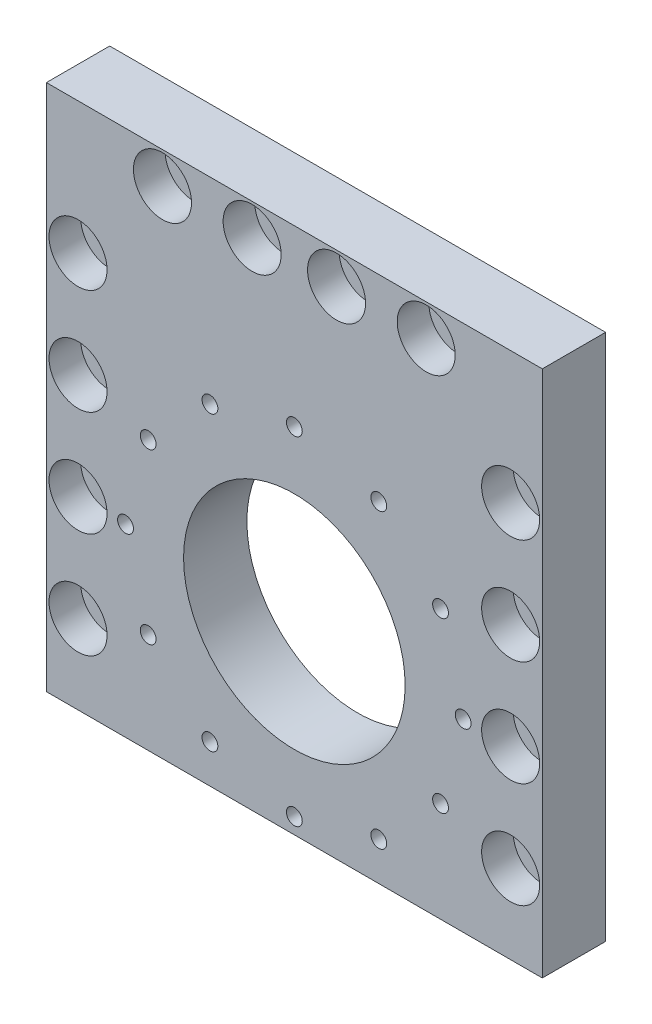
SolidWorks part; units mm, degrees
ref_plane "前视基准面" through (0, 0, 0) normal (0, 0, 1) x (1, 0, 0)
ref_plane "上视基准面" through (0, 0, 0) normal (0, 1, 0) x (1, 0, 0)
ref_plane "右视基准面" through (0, 0, 0) normal (1, 0, 0) x (0, 0, -1)
sketch "草图1" plane through (0, 0, 0) normal (0, 0, 1) x (1, 0, 0)
  line L1 (35, -35) -> (-35, -35)
  line L2 (35, -35) -> (35, 35)
  line L3 (35, 35) -> (-35, 35)
  line L4 (-35, -35) -> (-35, 35)
  line L5 (35, -35) -> (-35, 35) construction
  line L6 (35, 35) -> (-35, -35) construction
  circle A0 centre (0, 0) radius 21
  circle A1 centre (32, 0) radius 1.5
  circle A2 centre (27.7128, -16) radius 1.5
  circle A3 centre (16, -27.7128) radius 1.5
  circle A4 centre (0, -32) radius 1.5
  circle A5 centre (-16, -27.7128) radius 1.5
  circle A6 centre (-27.7128, -16) radius 1.5
  circle A7 centre (-32, 0) radius 1.5
  circle A8 centre (-27.7128, 16) radius 1.5
  circle A9 centre (-16, 27.7128) radius 1.5
  circle A10 centre (0, 32) radius 1.5
  circle A11 centre (16, 27.7128) radius 1.5
  circle A12 centre (27.7128, 16) radius 1.5
  point P0 (0, 0)
  dimension "D3" = 42
  dimension "D4" = 3
  dimension "D1" = 70
  dimension "D2" = 70
  dimension "D5" = 32
  dimension "D6" = 12
extrude "凸台-拉伸1" add sketch "草图1" along normal blind 12
sketch "草图3" plane through (0, 35, 0) normal (0, 1, 0) x (1, 0, 0)
  line L1 (-35, 0) -> (35, 0)
  line L2 (-35, 0) -> (-35, -12)
  line L3 (-35, -12) -> (35, -12)
  line L4 (35, 0) -> (35, -12)
extrude "凸台-拉伸2" add sketch "草图3" along normal blind 30
sketch "草图4" plane through (0, 0, 0) normal (0, 0, -1) x (-1, 0, 0)
  line L0 (-35, 65) -> (35, 65) construction
  line L1 (-35, -35) -> (-35, 65) construction
  line L2 (0, 61.4377) -> (0, 44.3718) construction
  circle A0 centre (-25, 59) radius 3
  circle A1 centre (-8, 59) radius 3
  circle A2 centre (25, 59) radius 3
  circle A3 centre (8, 59) radius 3
  dimension "D1" = 6
  dimension "D2" = 6
  dimension "D3" = 6
  dimension "D4" = 10
  dimension "D5" = 6
  dimension "D6" = 17
extrude "切除-拉伸2" cut sketch "草图4" against normal blind 12
sketch "草图7" plane through (0, 0, 12) normal (0, 0, 1) x (1, 0, 0)
  circle A2 centre (-25, 59) radius 5.5
  circle A3 centre (-25, 59) radius 5.5
  circle A5 centre (-8, 59) radius 5.5
  circle A6 centre (-8, 59) radius 5.5
  circle A8 centre (8, 59) radius 5.5
  circle A9 centre (8, 59) radius 5.5
  circle A11 centre (25, 59) radius 5.5
  circle A12 centre (25, 59) radius 5.5
  dimension "D1" = 2.5
  dimension "D2" = 2.5
  dimension "D3" = 2.5
  dimension "D4" = 2.5
extrude "切除-拉伸6" cut sketch "草图7" against normal blind 6
sketch "草图8" plane through (35, 0, 0) normal (1, 0, 0) x (0, 0, -1)
  line L1 (-12, 65) -> (0, 65)
  line L2 (-12, 65) -> (-12, -35)
  line L3 (-12, -35) -> (0, -35)
  line L4 (0, 65) -> (0, -35)
extrude "凸台-拉伸3" add sketch "草图8" along normal blind 12
sketch "草图11" plane through (-35, 0, 0) normal (-1, 0, 0) x (0, 0, 1)
  line L1 (0, 65) -> (12, 65)
  line L2 (0, 65) -> (0, -35)
  line L3 (0, -35) -> (12, -35)
  line L4 (12, 65) -> (12, -35)
extrude "凸台-拉伸4" add sketch "草图11" along normal blind 12
sketch "草图12" plane through (0, 0, 12) normal (0, 0, 1) x (1, 0, 0)
  line L0 (41, 54.0546) -> (41, -24.676) construction
  line L1 (-47, -35) -> (47, -35) construction
  line L2 (0, 0) -> (0, 36.0161) construction
  line L3 (47, 65) -> (47, -35) construction
  circle A0 centre (41, -20) radius 3
  circle A1 centre (41, 0) radius 3
  circle A2 centre (41, 20) radius 3
  circle A3 centre (41, 40) radius 3
  circle A4 centre (-41, -20) radius 3
  circle A5 centre (-41, 0) radius 3
  circle A6 centre (-41, 40) radius 3
  circle A7 centre (-41, 20) radius 3
  dimension "D1" = 6
  dimension "D2" = 6
  dimension "D3" = 6
  dimension "D4" = 6
  dimension "D5" = 15
  dimension "D6" = 20
  dimension "D7" = 20
  dimension "D8" = 20
  dimension "D9" = 6
extrude "切除-拉伸7" cut sketch "草图12" against normal blind 22
sketch "草图13" plane through (0, 0, 12) normal (0, 0, 1) x (1, 0, 0)
  line L0 (0, 0) -> (0, 39.1535) construction
  circle A2 centre (41, 40) radius 5.5
  circle A3 centre (41, 40) radius 5.5
  circle A5 centre (41, 20) radius 5.5
  circle A6 centre (41, 20) radius 5.5
  circle A8 centre (41, 0) radius 5.5
  circle A9 centre (41, 0) radius 5.5
  circle A10 centre (-41, -20) radius 5.5
  circle A11 centre (41, -20) radius 5.5
  circle A12 centre (41, -20) radius 5.5
  circle A13 centre (-41, 0) radius 5.5
  circle A14 centre (-41, 20) radius 5.5
  circle A15 centre (-41, 40) radius 5.5
  dimension "D1" = 2.5
  dimension "D2" = 2.5
  dimension "D3" = 2.5
  dimension "D4" = 2.5
extrude "切除-拉伸8" cut sketch "草图13" against normal blind 6
sketch "草图14" plane through (0, -35, 0) normal (0, -1, 0) x (1, 0, 0)
  line L0 (-47, 0) -> (-47, 12) construction
  line L1 (0, 9.7468) -> (0, 2.0877) construction
  circle A0 centre (-33, 6) radius 3
  circle A1 centre (-8, 6) radius 3
  circle A2 centre (33, 6) radius 3
  circle A3 centre (8, 6) radius 3
  dimension "D1" = 6
  dimension "D2" = 6
  dimension "D3" = 14
  dimension "D4" = 25
extrude "切除-拉伸9" cut sketch "草图14" against normal blind 10
